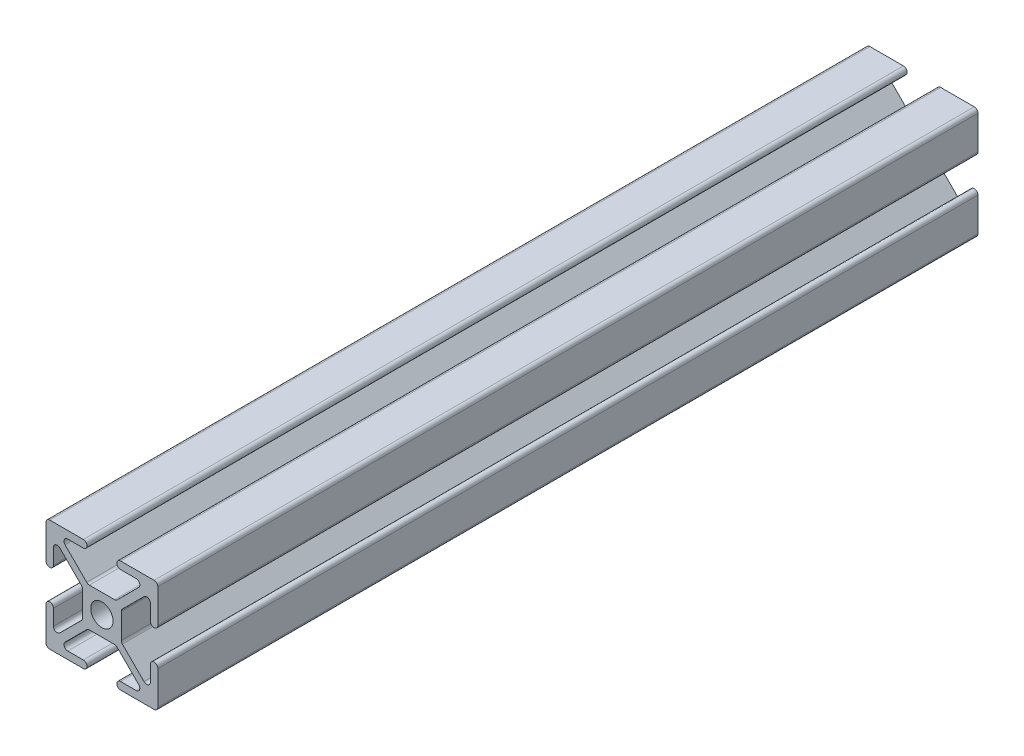
SolidWorks part; units mm, degrees
ref_plane "Alzado" through (0, 0, 0) normal (0, 0, 1) x (1, 0, 0)
ref_plane "Planta" through (0, 0, 0) normal (0, 1, 0) x (1, 0, 0)
ref_plane "Vista lateral" through (0, 0, 0) normal (1, 0, 0) x (0, 0, -1)
sketch "Croquis1" plane through (0, 0, 0) normal (0, 0, 1) x (1, 0, 0)
  line L1 (-14, 15) -> (14, 15)
  line L2 (-15, 14) -> (-15, -14)
  line L3 (-14, -15) -> (14, -15)
  line L4 (15, 14) -> (15, -14)
  line L5 (-15, 15) -> (15, -15) construction
  line L6 (-15, -15) -> (15, 15) construction
  arc A0 (-14, 15) -> (-15, 14) centre (-14, 14) ccw
  arc A1 (14, -15) -> (15, -14) centre (14, -14) ccw
  arc A2 (-14, -15) -> (-15, -14) centre (-14, -14) cw
  arc A3 (15, 14) -> (14, 15) centre (14, 14) ccw
  point P0 (0, 0)
  dimension "D3" = 1
  dimension "D4" = 1
  dimension "D1" = 30
  dimension "D2" = 30
extrude "Saliente-Extruir1" add sketch "Croquis1" against normal blind 220
sketch "Croquis2" plane through (0, 0, 0) normal (0, 0, 1) x (1, 0, 0)
  circle A0 centre (0, 0) radius 3
  dimension "D1" = 6
sketch "Croquis3" plane through (0, 0, 0) normal (0, 0, 1) x (1, 0, 0)
  line L0 (-15, 0) -> (15, 0) construction
  line L1 (4.0787, -5.4929) -> (9.8787, -11.2929)
  line L2 (-11.2929, 9.8787) -> (-5.4929, 4.0787)
  line L3 (-9.8787, 11.2929) -> (-4.0787, 5.4929)
  line L4 (-13, 9.1716) -> (-13, 5)
  line L5 (-15, 14) -> (-15, -14) construction
  line L6 (-5.2, 3.3716) -> (-5.2, -3.3716)
  line L7 (-9.1716, 13) -> (-5, 13)
  line L8 (9.8787, 11.2929) -> (4.0787, 5.4929)
  line L9 (11.2929, 9.8787) -> (5.4929, 4.0787)
  line L10 (-3.3716, 5.2) -> (3.3716, 5.2)
  line L11 (14, 15) -> (-14, 15) construction
  line L12 (13, 9.1716) -> (13, 5)
  line L13 (5.2, 3.3716) -> (5.2, -3.3716)
  line L14 (15, -14) -> (15, 14) construction
  line L15 (-9.1716, -13) -> (-5, -13)
  line L16 (-3.3716, -5.2) -> (3.3716, -5.2)
  line L17 (-14, -15) -> (14, -15) construction
  line L18 (-5.4929, -4.0787) -> (-11.2929, -9.8787)
  line L19 (5.4929, -4.0787) -> (11.2929, -9.8787)
  line L20 (-4.0787, -5.4929) -> (-9.8787, -11.2929)
  line L21 (5, -13) -> (9.1716, -13)
  line L22 (-13, -5) -> (-13, -9.1716)
  line L23 (13, -5) -> (13, -9.1716)
  line L24 (0, 15) -> (0, -5.2) construction
  line L34 (5, 13) -> (9.1716, 13)
  arc A0 (9.8787, 11.2929) -> (9.1716, 13) centre (9.1716, 12) ccw
  arc A1 (-9.8787, 11.2929) -> (-9.1716, 13) centre (-9.1716, 12) cw
  arc A2 (9.8787, 11.2929) -> (9.1716, 13) centre (9.1716, 12) ccw
  arc A3 (13, 9.1716) -> (11.2929, 9.8787) centre (12, 9.1716) ccw
  arc A4 (11.2929, -9.8787) -> (13, -9.1716) centre (12, -9.1716) ccw
  arc A5 (9.1716, -13) -> (9.8787, -11.2929) centre (9.1716, -12) ccw
  arc A6 (-9.1716, -13) -> (-9.8787, -11.2929) centre (-9.1716, -12) cw
  arc A7 (-11.2929, -9.8787) -> (-13, -9.1716) centre (-12, -9.1716) cw
  arc A8 (-13, 9.1716) -> (-11.2929, 9.8787) centre (-12, 9.1716) cw
  arc A9 (-4.0787, -5.4929) -> (-3.3716, -5.2) centre (-3.3716, -6.2) cw
  arc A10 (3.3716, -5.2) -> (4.0787, -5.4929) centre (3.3716, -6.2) cw
  arc A11 (5.4929, -4.0787) -> (5.2, -3.3716) centre (6.2, -3.3716) cw
  arc A12 (5.2, 3.3716) -> (5.4929, 4.0787) centre (6.2, 3.3716) cw
  arc A13 (3.3716, 5.2) -> (4.0787, 5.4929) centre (3.3716, 6.2) ccw
  arc A14 (-3.3716, 5.2) -> (-4.0787, 5.4929) centre (-3.3716, 6.2) cw
  arc A15 (-5.4929, -4.0787) -> (-5.2, -3.3716) centre (-6.2, -3.3716) ccw
  arc A16 (-5.2, 3.3716) -> (-5.4929, 4.0787) centre (-6.2, 3.3716) ccw
  circle A17 centre (-14, -5) radius 1
  circle A18 centre (-14, 5) radius 1
  circle A19 centre (-5, -14) radius 1
  circle A20 centre (5, -14) radius 1
  circle A21 centre (14, 5) radius 1
  circle A22 centre (14, -5) radius 1
  circle A23 centre (-5, 14) radius 1
  circle A24 centre (5, 14) radius 1
  point P20 (-11.5858, -13)
  point P30 (-13, -11.5858)
  point P43 (-3.7858, -5.2)
  point P50 (3.7858, -5.2)
  point P53 (5.2, -3.7858)
  point P62 (-5.2, -3.7858)
  line M2 (-15, 14) -> (-15, -14)
  line M4 (-14, -15) -> (14, -15)
  line M6 (15, -14) -> (15, 14)
  line M8 (14, 15) -> (-14, 15)
  dimension "D6" = 9.8
  dimension "D7" = 2
  dimension "D12" = 2
  dimension "D19" = 1
  dimension "D2" = 1
  dimension "D3" = 1
  dimension "D4" = 1
  dimension "D16" = 1
  dimension "D5" = 2
  dimension "D8" = 9.8
  dimension "D9" = 2
  dimension "D10" = 9.8
  dimension "D11" = 9.8
  dimension "D15" = 1
  dimension "D20" = 1
  dimension "D23" = 1
  dimension "D24" = 1
  dimension "D27" = 1
  dimension "D28" = 1
extrude "Cortar-Extruir1" cut sketch "Croquis2" against normal through all
extrude "Cortar-Extruir3" cut sketch "Croquis3" against normal through all contours A18 A17 L22 A7 L18 A15 L6 A16 L2 A8 L4 M2 | A24 A23 L7 A1 L3 A14 L10 A13 L8 A0 L34 M8 | A20 L21 A5 L1 A10 L16 A9 L20 A6 L15 A19 M4 | A22 A21 L12 A3 L9 A12 L13 A11 L19 A4 L23 M6
